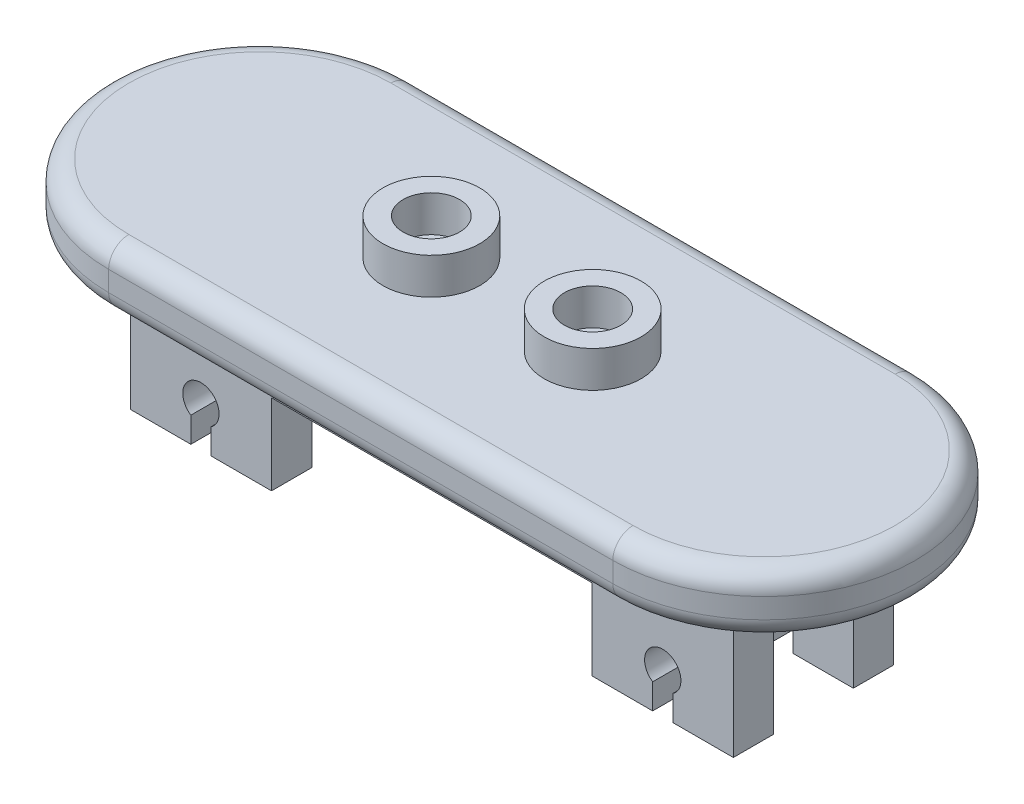
SolidWorks part; units mm, degrees
ref_plane "Front Plane" through (0, 0, 0) normal (0, 0, 1) x (1, 0, 0)
ref_plane "Top Plane" through (0, 0, 0) normal (0, 1, 0) x (1, 0, 0)
ref_plane "Right Plane" through (0, 0, 0) normal (1, 0, 0) x (0, 0, -1)
sketch "Sketch1" plane through (0, 0, 0) normal (0, 1, 0) x (1, 0, 0)
  line L1 (-12.5, -7.5) -> (12.5, -7.5)
  line L3 (-12.5, 7.5) -> (12.5, 7.5)
  line L5 (-12.5, -7.5) -> (12.5, 7.5) construction
  line L6 (-12.5, 7.5) -> (12.5, -7.5) construction
  arc A0 (-12.5, 7.5) -> (-12.5, -7.5) centre (-12.5, 0) ccw
  arc A1 (12.5, -7.5) -> (12.5, 7.5) centre (12.5, 0) ccw
  point P0 (0, 0)
  dimension "D1" = 25
  dimension "D2" = 15
extrude "Boss-Extrude1" add sketch "Sketch1" along normal blind 3
fillet "Fillet1" radius 1 8 edges at (0, 3, -7.5) (20, 3, 0) (0, 3, 7.5) (0, 0, -7.5) (20, 0, 0) (0, 0, 7.5) (-20, 3, 0) (-20, 0, 0)
sketch "Sketch20" plane through (0, 0, 0) normal (0, -1, 0) x (1, 0, 0)
  line L1 (-7.95, -3.975) -> (7.95, -3.975)
  line L2 (-7.95, -3.975) -> (-7.95, 3.975)
  line L3 (-7.95, 3.975) -> (7.95, 3.975)
  line L4 (7.95, -3.975) -> (7.95, 3.975)
  line L5 (-7.95, -3.975) -> (7.95, 3.975) construction
  line L6 (-7.95, 3.975) -> (7.95, -3.975) construction
  point P0 (0, 0)
  dimension "D1" = 7.95
  dimension "D2" = 15.9
extrude "Boss-Extrude2" add sketch "Sketch20" along normal blind 3
shell "Shell1" thickness 1.2
sketch "Sketch21" plane through (0, 0, 0) normal (0, -1, 0) x (1, 0, 0)
  line L0 (7.95, -3.975) -> (14.95, -3.975)
  line L1 (14.95, -3.975) -> (14.95, -1.975)
  line L2 (14.95, -1.975) -> (7.95, -1.975)
  line L3 (7.95, -3.975) -> (7.95, 3.975) construction
  line L4 (7.95, 3.975) -> (14.95, 3.975)
  line L5 (14.95, 3.975) -> (14.95, 1.975)
  line L6 (14.95, 1.975) -> (7.95, 1.975)
  line M11 (7.95, 3.975) -> (7.95, -3.975)
  dimension "D1" = 7
  dimension "D2" = 2
extrude "Boss-Extrude4" add sketch "Sketch21" along normal blind 7 contours L1 L2 L0 M11 | L6 L5 L4 M11
sketch "Sketch22" plane through (0, 0, 3.975) normal (0, 0, 1) x (1, 0, 0)
  line L0 (7.95, -3) -> (14.95, -7) construction
  line L1 (14.95, -7) -> (7.95, -7) construction
  line L2 (7.95, -7) -> (14.95, -3) construction
  line L3 (14.95, -7) -> (14.95, 0) construction
  line L4 (14.95, -3) -> (7.95, -3) construction
  line L5 (11.45, -5) -> (11.45, -9) construction
  line L6 (11.95, -7) -> (10.95, -7)
  line L7 (7.95, -7) -> (14.95, -7) construction
  line L8 (11.95, -7) -> (11.95, -5.7483)
  line L9 (10.95, -7) -> (10.95, -5.7483)
  arc A0 (11.95, -5.7483) -> (10.95, -5.7483) centre (11.45, -5) ccw
  point P17 (11.45, -7)
  dimension "D1" = 1.8
  dimension "D2" = 1
extrude "Cut-Extrude1" cut sketch "Sketch22" against normal through all
mirror "Mirror1" about plane through (0, 0, 0) normal (1, 0, 0) of "Boss-Extrude4", "Cut-Extrude1"
sketch "Sketch23" plane through (0, 3, 0) normal (0, 1, 0) x (1, 0, 0)
  line L0 (-4, 0) -> (4, 0) construction
  circle A0 centre (-4, 0) radius 2.4
  circle A1 centre (-4, 0) radius 1.4
  point P4 (0, 0)
  dimension "D2" = 4.8
  dimension "D3" = 1
  dimension "D1" = 8
extrude "Boss-Extrude5" add sketch "Sketch23" along normal blind 1.8
mirror "Mirror2" about plane through (0, 0, 0) normal (1, 0, 0) of "Boss-Extrude5"
